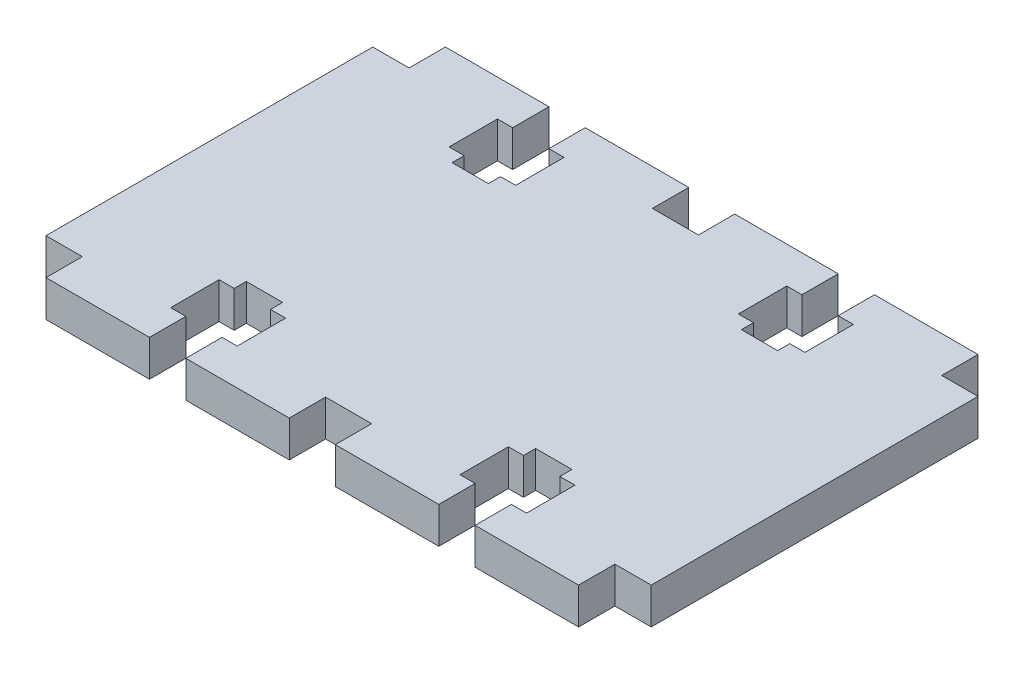
SolidWorks part; units mm, degrees
ref_plane "前视基准面" through (0, 0, 0) normal (0, 0, 1) x (1, 0, 0)
ref_plane "上视基准面" through (0, 0, 0) normal (0, 1, 0) x (1, 0, 0)
ref_plane "右视基准面" through (0, 0, 0) normal (1, 0, 0) x (0, 0, -1)
other "Configuration Table"
sketch "草图1" plane through (0, 0, 0) normal (0, 1, 0) x (1, 0, 0)
  line L0 (25, 0) -> (25, -27)
  line L1 (0, 0) -> (50, 0)
  line L2 (0, 0) -> (0, -27)
  line L3 (0, -27) -> (50, -27)
  line L4 (50, 0) -> (50, -27)
  line L5 (3, -27) -> (23.0981, -27)
  line L6 (3, -27) -> (3, -30)
  line L7 (3, -30) -> (23.0981, -30)
  line L8 (23.0981, -27) -> (23.0981, -30)
  line L13 (38.4509, -22) -> (35.4509, -22)
  line L14 (11.5491, -30) -> (14.5491, -30)
  line L19 (11.5491, -30) -> (11.5491, -22)
  line L20 (11.5491, -22) -> (14.5491, -22)
  line L33 (0, -13.5) -> (50, -13.5)
  line L54 (3, 3) -> (23.0981, 3)
  line L55 (23.0981, 0) -> (23.0981, 3)
  line L56 (3, 0) -> (23.0981, 0)
  line L57 (3, 0) -> (3, 3)
  line L58 (14.5491, -30) -> (14.5491, -22)
  line L59 (10.2991, -23) -> (15.7991, -23)
  line L60 (10.2991, -23) -> (10.2991, -27)
  line L61 (10.2991, -27) -> (15.7991, -27)
  line L62 (15.7991, -23) -> (15.7991, -27)
  line L63 (35.4509, -30) -> (35.4509, -22)
  line L64 (38.4509, -30) -> (35.4509, -30)
  line L65 (38.4509, -30) -> (38.4509, -22)
  line L66 (39.7009, -27) -> (34.2009, -27)
  line L67 (34.2009, -23) -> (34.2009, -27)
  line L68 (39.7009, -23) -> (34.2009, -23)
  line L69 (39.7009, -23) -> (39.7009, -27)
  line L70 (39.7009, -4) -> (39.7009, 0)
  line L71 (39.7009, -4) -> (34.2009, -4)
  line L72 (34.2009, -4) -> (34.2009, 0)
  line L73 (39.7009, 0) -> (34.2009, 0)
  line L74 (38.4509, 3) -> (38.4509, -5)
  line L75 (38.4509, 3) -> (35.4509, 3)
  line L76 (35.4509, 3) -> (35.4509, -5)
  line L77 (38.4509, -5) -> (35.4509, -5)
  line L78 (10.2991, 0) -> (15.7991, 0)
  line L79 (15.7991, -4) -> (15.7991, 0)
  line L80 (10.2991, -4) -> (15.7991, -4)
  line L81 (10.2991, -4) -> (10.2991, 0)
  line L82 (11.5491, -5) -> (14.5491, -5)
  line L83 (14.5491, 3) -> (14.5491, -5)
  line L84 (11.5491, 3) -> (14.5491, 3)
  line L85 (11.5491, 3) -> (11.5491, -5)
  line L86 (47, -30) -> (26.9019, -30)
  line L87 (26.9019, -27) -> (26.9019, -30)
  line L88 (47, -27) -> (26.9019, -27)
  line L89 (47, -27) -> (47, -30)
  line L90 (47, 0) -> (47, 3)
  line L91 (47, 0) -> (26.9019, 0)
  line L92 (26.9019, 0) -> (26.9019, 3)
  line L93 (47, 3) -> (26.9019, 3)
  point P15 (13.0491, -30)
  dimension "D3" = 3
  dimension "D4" = 8
  dimension "D1" = 50
  dimension "D2" = 27
  dimension "D6" = 4
  dimension "D7" = 3
  dimension "D8" = 3
  dimension "D9" = 2.75
  dimension "D10" = 0
  dimension "D11" = 1.5
  dimension "D5" = 5.5
extrude "凸台-拉伸1" add sketch "草图1" along normal blind 3
